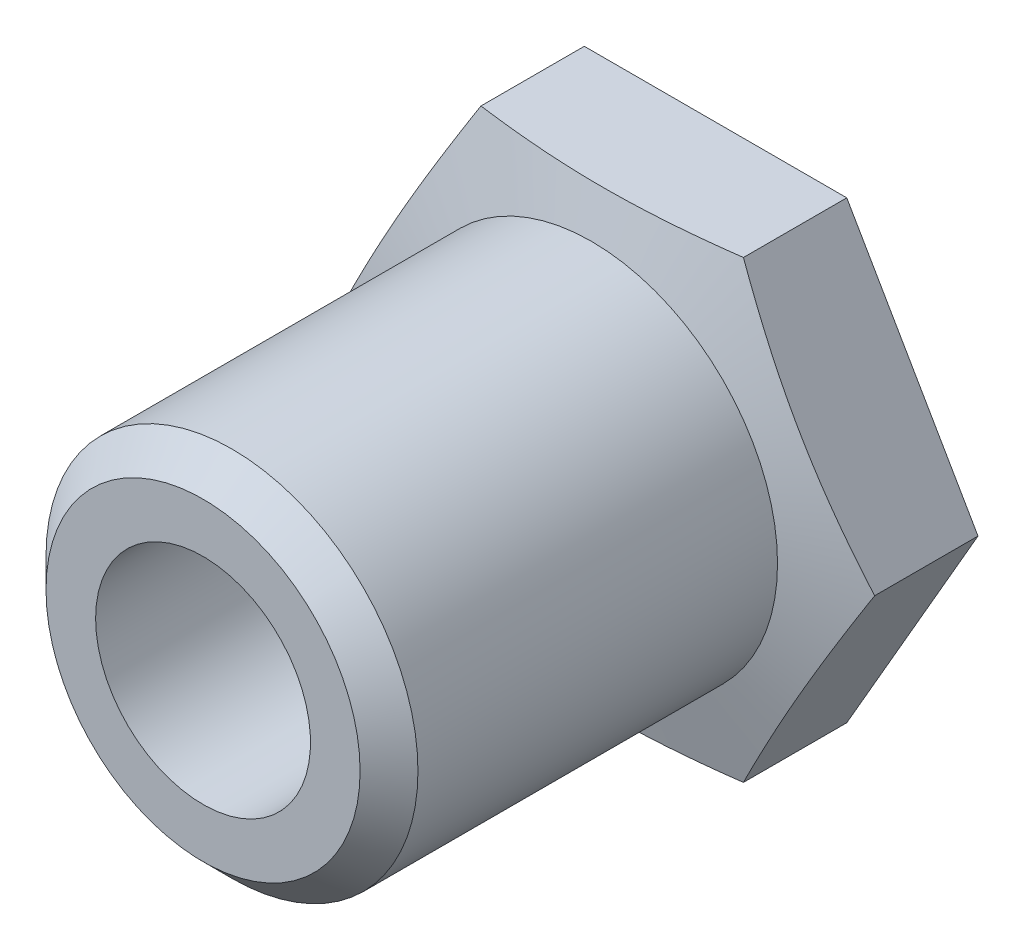
SolidWorks part; units mm, degrees
material "Brass"
ref_plane "Front Plane" through (0, 0, 0) normal (0, 0, 1) x (1, 0, 0)
ref_plane "Top Plane" through (0, 0, 0) normal (0, 1, 0) x (1, 0, 0)
ref_plane "Right Plane" through (0, 0, 0) normal (1, 0, 0) x (0, 0, -1)
sketch "Sketch1" plane through (0, 0, 0) normal (0, 0, 1) x (1, 0, 0)
  line L1 (6.3509, 0) -> (3.1754, 5.5)
  line L2 (3.1754, 5.5) -> (-3.1754, 5.5)
  line L3 (-3.1754, 5.5) -> (-6.3509, 0)
  line L4 (-6.3509, 0) -> (-3.1754, -5.5)
  line L5 (-3.1754, -5.5) -> (3.1754, -5.5)
  line L6 (3.1754, -5.5) -> (6.3509, 0)
  circle A0 centre (0, 0) radius 5.5 construction
  dimension "D1" = 11
extrude "Boss-Extrude1" add sketch "Sketch1" along normal blind 3
sketch "Sketch2" plane through (0, 0, 3) normal (0, 0, 1) x (1, 0, 0)
  circle A0 centre (0, 0) radius 4.5
  dimension "D1" = 9
extrude "Boss-Extrude2" add sketch "Sketch2" along normal blind 9.4
sketch "Sketch3" plane through (0, 0, 0) normal (0, 0, -1) x (-1, 0, 0)
  circle A0 centre (0, 0) radius 2.6
  dimension "D1" = 5.2
extrude "Cut-Extrude1" cut sketch "Sketch3" against normal through all from offset 2 offset against normal yes
ref_plane "Insertion extent" through (0, 0, 6) normal (0, 0, 1) x (1, 0, 0)
ref_axis "Longitudinal" through (0, 0, 12.4) along (0, 0, -1)
sketch "Sketch5" plane through (0, 0, 0) normal (0, 1, 0) x (1, 0, 0)
  line L0 (-4.5, -3) -> (-6.3509, -3)
  line L1 (-3.1754, -3) -> (-6.3509, -3) construction
  line L2 (-4.5, -3) -> (-4.5, -12.4) construction
  line L3 (-6.3509, -3) -> (-6.3509, -2.5)
  line L4 (-6.3509, -3) -> (-6.3509, 0) construction
  line L5 (-6.3509, -2.5) -> (-4.5, -3)
  dimension "D1" = 0.5
revolve "Cut-Revolve2" cut sketch "Sketch5" angle 360 about axis through (0, 0, 12.4) along (0, 0, -1)
chamfer "Chamfer2" distance 0.7 angle 45 1 edges at (4.5, 0, 12.4)
